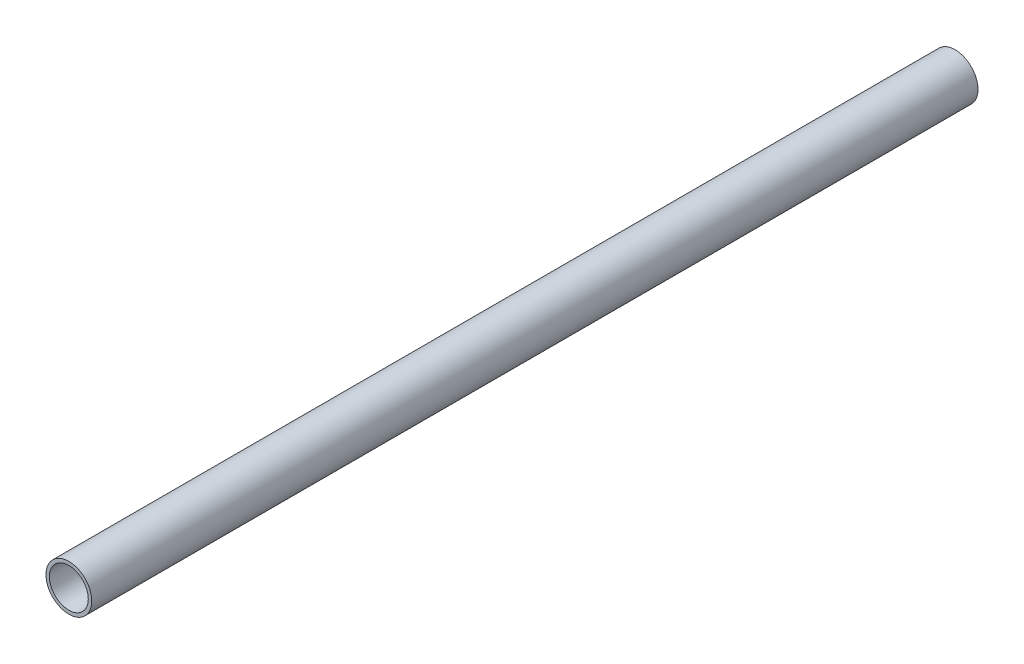
SolidWorks part; units mm, degrees
material "Hexcel AS4C (3000 Filaments)"
ref_plane "Plan de face" through (0, 0, 0) normal (0, 0, 1) x (1, 0, 0)
ref_plane "Plan de dessus" through (0, 0, 0) normal (0, 1, 0) x (1, 0, 0)
ref_plane "Plan de droite" through (0, 0, 0) normal (1, 0, 0) x (0, 0, -1)
sketch "Esquisse1" plane through (0, 0, 0) normal (0, 0, 1) x (1, 0, 0)
  circle A0 centre (0, 0) radius 2.97
  dimension "D1" = 5.94
extrude "Boss.-Extru.1" add sketch "Esquisse1" along normal blind 115
sketch "Esquisse2" plane through (0, 0, 115) normal (0, 0, 1) x (1, 0, 0)
  circle A0 centre (0, 0) radius 2.52
  circle A2 centre (0, 0) radius 2.97 construction
  dimension "D1" = 0.45
extrude "Enlèv. mat.-Extru.1" cut sketch "Esquisse2" against normal through all
